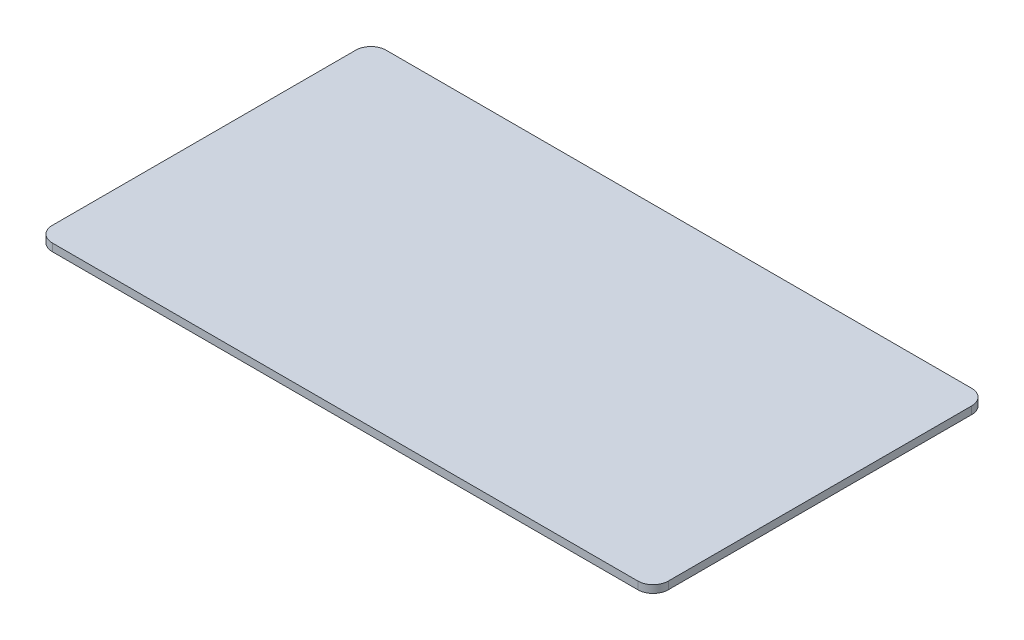
SolidWorks part; units mm, degrees
ref_plane "Plan de face" through (0, 0, 0) normal (0, 0, 1) x (1, 0, 0)
ref_plane "Plan de dessus" through (0, 0, 0) normal (0, 1, 0) x (1, 0, 0)
ref_plane "Plan de droite" through (0, 0, 0) normal (1, 0, 0) x (0, 0, -1)
sketch "Esquisse1" plane through (0, 0, 0) normal (0, 1, 0) x (1, 0, 0)
  line L1 (-60.8, 32.95) -> (60.8, 32.95)
  line L2 (-60.8, 32.95) -> (-60.8, -32.95)
  line L3 (-60.8, -32.95) -> (60.8, -32.95)
  line L4 (60.8, 32.95) -> (60.8, -32.95)
  line L5 (-60.8, 32.95) -> (60.8, -32.95) construction
  line L6 (-60.8, -32.95) -> (60.8, 32.95) construction
  point P0 (0, 0)
  dimension "D1" = 121.6
  dimension "D2" = 65.9
extrude "Boss.-Extru.1" add sketch "Esquisse1" along normal blind 1.5
fillet "Congé1" radius 3 4 edges at (60.8, 0.75, 32.95) (60.8, 0.75, -32.95) (-60.8, 0.75, -32.95) (-60.8, 0.75, 32.95)
